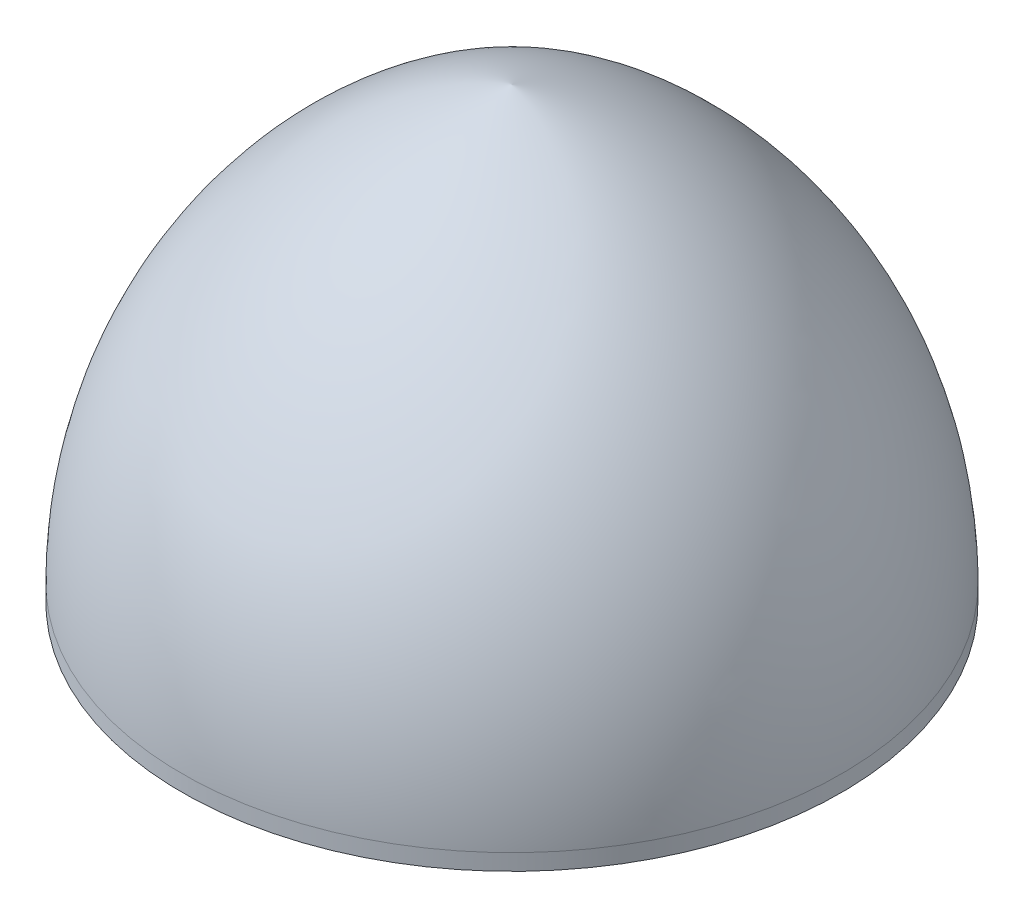
SolidWorks part; units mm, degrees
ref_plane "Front Plane" through (0, 0, 0) normal (0, 0, 1) x (1, 0, 0)
ref_plane "Top Plane" through (0, 0, 0) normal (0, 1, 0) x (1, 0, 0)
ref_plane "Right Plane" through (0, 0, 0) normal (1, 0, 0) x (0, 0, -1)
sketch "Sketch1" plane through (0, 0, 0) normal (0, 0, 1) x (1, 0, 0)
  line L1 (58, 170) -> (58, 167)
  line L4 (61, 170) -> (61, 167)
  line L5 (0, 246.8846) -> (0, 250)
  line L9 (58, 167) -> (61, 167)
  line L10 (0, 0) -> (0, 250) construction
  line L15 (58, 0) -> (58, 170) construction
  line L16 (61, 0) -> (61, 170) construction
  line L18 (58, 170) -> (55, 170)
  line L19 (58, 170) -> (58, 167)
  line L20 (58, 167) -> (55, 167)
  line L21 (55, 170) -> (55, 167)
  arc A0 (61, 170) -> (0, 250) centre (-21.959, 170) ccw
  arc A1 (58, 170) -> (0, 246.8846) centre (-21.959, 170) ccw
  arc A8 (58, 170) -> (-0.7941, 247.107) centre (-21.959, 170) ccw construction
  dimension "D1" = 3
  dimension "D2" = 170
  dimension "D3" = 80
  dimension "D8" = 3
  dimension "D5" = 61
  dimension "D4" = 3
revolve "Revolve7" add sketch "Sketch1" angle 360 about L10
sketch "Sketch2" plane through (0, 0, 0) normal (0, 0, 1) x (1, 0, 0)
  line L0 (61, 170) -> (52, 170)
  line L1 (61, 170) -> (-61, 170) construction
  line L2 (52, 170) -> (52, 167)
  line L3 (52, 167) -> (58, 167)
  line L4 (58, 167) -> (58, 170)
  line L5 (0, 250) -> (0, 167) construction
  line L6 (-61, 167) -> (61, 167) construction
  line L7 (-58, 167) -> (-58, 170)
  line L8 (-52, 170) -> (-52, 167)
  line L9 (-61, 170) -> (-52, 170)
  line L10 (-52, 167) -> (-58, 167)
  line L11 (61, 167) -> (61, 170) construction
  point P22 (0, 0)
  dimension "D1" = 9
  dimension "D2" = 3
  dimension "D3" = 3
revolve "Revolve8" add sketch "Sketch2" angle 3 about L5
sketch "Sketch3" plane through (0, 0, 0) normal (0, 0, 1) x (1, 0, 0)
  line L0 (61, 170) -> (49, 170)
  line L1 (61, 170) -> (-61, 170) construction
  line L2 (49, 170) -> (49, 167)
  line L3 (49, 167) -> (52, 167)
  line L4 (52, 167) -> (52, 170)
  line L5 (0, 250) -> (0, 167) construction
  line L6 (-61, 167) -> (61, 167) construction
  line L7 (-52, 167) -> (-52, 170)
  line L8 (-61, 170) -> (-49, 170)
  line L9 (-49, 170) -> (-49, 167)
  line L10 (-49, 167) -> (-52, 167)
  dimension "D1" = 12
  dimension "D2" = 3
  dimension "D3" = 3
revolve "Revolve9" add sketch "Sketch3" angle 15 about L5
